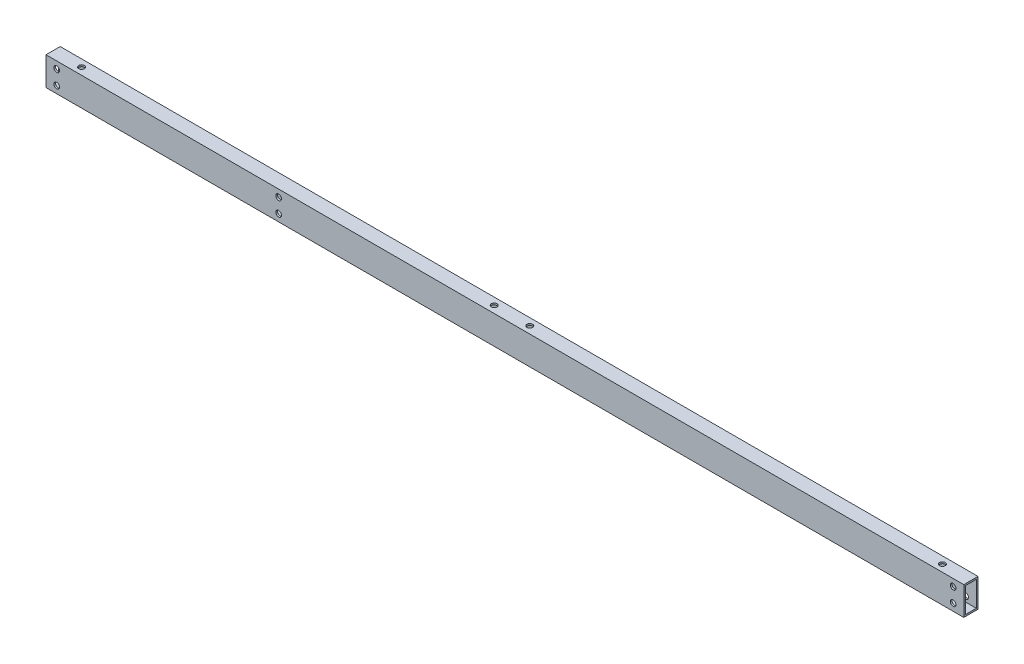
SolidWorks part; units mm, degrees
material "5052-H34"
ref_plane "正面" through (0, 0, 0) normal (0, 0, 1) x (1, 0, 0)
ref_plane "平面" through (0, 0, 0) normal (0, 1, 0) x (1, 0, 0)
ref_plane "右側面" through (0, 0, 0) normal (1, 0, 0) x (0, 0, -1)
sketch "ｽｹｯﾁ1" plane through (0, 0, 0) normal (1, 0, 0) x (0, 0, -1)
  line L1 (-5, 10) -> (5, 10)
  line L2 (-5, 10) -> (-5, -10)
  line L3 (-5, -10) -> (5, -10)
  line L4 (5, 10) -> (5, -10)
  line L5 (-5, 10) -> (5, -10) construction
  line L6 (-5, -10) -> (5, 10) construction
  point P0 (0, 0)
  dimension "D1" = 10
  dimension "D2" = 20
extrude "押し出し-薄板1" add sketch "ｽｹｯﾁ1" along normal blind 645 thin
sketch "ｽｹｯﾁ2" plane through (0, 0, 5) normal (0, 0, 1) x (1, 0, 0)
  line L0 (322.5, 10) -> (322.5, -10) construction
  line L1 (645, 10) -> (0, 10) construction
  line L2 (645, -10) -> (0, -10) construction
  line L3 (645, 0) -> (481.5, 0) construction
  line L4 (645, 10) -> (645, -10) construction
  circle A2 centre (163.5, -5) radius 2
  circle A3 centre (163.5, 5) radius 2
  circle A4 centre (637.5, 5) radius 2
  circle A5 centre (637.5, -5) radius 2
  circle A6 centre (7.5, -5) radius 2
  circle A7 centre (7.5, 5) radius 2
  dimension "D4" = 10
  dimension "D5" = 7.5
  dimension "D6" = 4
  dimension "D2" = 163.5
extrude "ｶｯﾄ - 押し出し1" cut sketch "ｽｹｯﾁ2" against normal through all
sketch "ｽｹｯﾁ3" plane through (0, 10, 0) normal (0, 1, 0) x (1, 0, 0)
  line L0 (322.5, 5) -> (322.5, -5) construction
  line L1 (645, 5) -> (0, 5) construction
  line L2 (645, -5) -> (0, -5) construction
  line L3 (0, 0) -> (20, 0) construction
  line L4 (0, 5) -> (0, -5) construction
  circle A4 centre (20, 0) radius 2
  circle A5 centre (625, 0) radius 2
  circle A6 centre (310, 0) radius 2
  circle A7 centre (335, 0) radius 2
  dimension "D1" = 4
  dimension "D6" = 5
  dimension "D7" = 25
  dimension "D8" = 4
  dimension "D2" = 20
extrude "ｶｯﾄ - 押し出し2" cut sketch "ｽｹｯﾁ3" against normal through all
